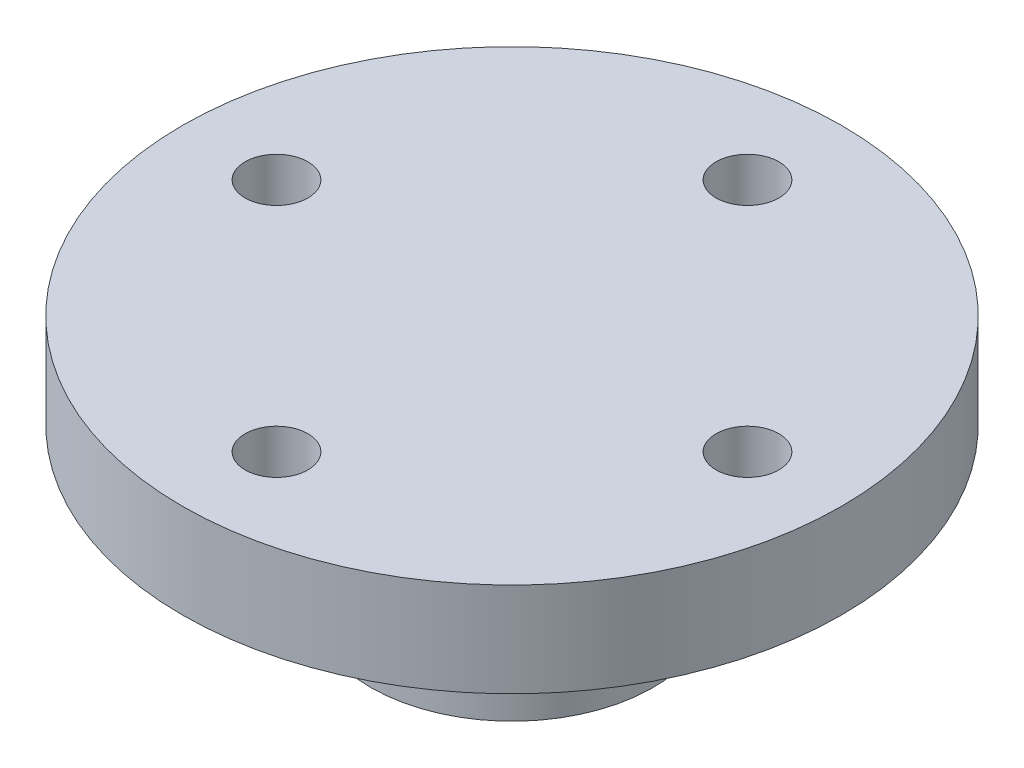
SolidWorks part; units mm, degrees
material "CA"
ref_plane "前视基准面" through (0, 0, 0) normal (0, 0, 1) x (1, 0, 0)
ref_plane "上视基准面" through (0, 0, 0) normal (0, 1, 0) x (1, 0, 0)
ref_plane "右视基准面" through (0, 0, 0) normal (1, 0, 0) x (0, 0, -1)
sketch "草图1" plane through (0, 0, 0) normal (0, 1, 0) x (1, 0, 0)
  circle A0 centre (0, 0) radius 4.5
  dimension "D1" = 9
extrude "凸台-拉伸1" add sketch "草图1" along normal blind 8
sketch "草图2" plane through (0, 8, 0) normal (0, 1, 0) x (1, 0, 0)
  circle A0 centre (0, 0) radius 10.5
  dimension "D1" = 21
extrude "凸台-拉伸2" add sketch "草图2" against normal blind 3
sketch "草图3" plane through (0, 0, 0) normal (0, -1, 0) x (1, 0, 0)
  circle A0 centre (0, 0) radius 2.8
  dimension "D1" = 5.6
extrude "切除-拉伸1" cut sketch "草图3" against normal blind 2.5
sketch "草图4" plane through (0, 0, 0) normal (0, -1, 0) x (1, 0, 0)
  line L0 (0.1306, 2.8722) -> (0.2304, 2.866)
  line L1 (-0.05, 2.8748) -> (0.05, 2.8748)
  line L2 (-0.05, 2.8748) -> (-0.05, 2.7252)
  line L3 (-0.05, 2.7252) -> (0.05, 2.7252)
  line L4 (0.05, 2.8748) -> (0.05, 2.7252)
  line L5 (-0.05, 2.8748) -> (0.05, 2.7252) construction
  line L6 (-0.05, 2.7252) -> (0.05, 2.8748) construction
  line L7 (0.1306, 2.8722) -> (0.1212, 2.723)
  line L8 (0.2304, 2.866) -> (0.221, 2.7167)
  line L9 (0.1212, 2.723) -> (0.221, 2.7167)
  line L10 (0.3107, 2.8584) -> (0.4099, 2.8458)
  line L11 (0.3107, 2.8584) -> (0.292, 2.71)
  line L12 (0.4099, 2.8458) -> (0.3912, 2.6975)
  line L13 (0.292, 2.71) -> (0.3912, 2.6975)
  line L14 (0.4896, 2.8332) -> (0.5878, 2.8145)
  line L15 (0.4896, 2.8332) -> (0.4615, 2.6863)
  line L16 (0.5878, 2.8145) -> (0.5598, 2.6676)
  line L17 (0.4615, 2.6863) -> (0.5598, 2.6676)
  line L18 (0.6665, 2.7969) -> (0.7634, 2.772)
  line L19 (0.6665, 2.7969) -> (0.6293, 2.6521)
  line L20 (0.7634, 2.772) -> (0.7262, 2.6272)
  line L21 (0.6293, 2.6521) -> (0.7262, 2.6272)
  line L22 (0.8408, 2.7495) -> (0.9359, 2.7186)
  line L23 (0.8408, 2.7495) -> (0.7946, 2.6073)
  line L24 (0.9359, 2.7186) -> (0.8897, 2.5764)
  line L25 (0.7946, 2.6073) -> (0.8897, 2.5764)
  line L26 (1.0118, 2.6913) -> (1.1048, 2.6545)
  line L27 (1.0118, 2.6913) -> (0.9567, 2.5523)
  line L28 (1.1048, 2.6545) -> (1.0497, 2.5155)
  line L29 (0.9567, 2.5523) -> (1.0497, 2.5155)
  line L30 (1.1788, 2.6225) -> (1.2693, 2.5799)
  line L31 (1.1788, 2.6225) -> (1.1151, 2.4872)
  line L32 (1.2693, 2.5799) -> (1.2056, 2.4446)
  line L33 (1.1151, 2.4872) -> (1.2056, 2.4446)
  line L34 (1.3411, 2.5433) -> (1.4287, 2.4951)
  line L35 (1.3411, 2.5433) -> (1.2691, 2.4122)
  line L36 (1.4287, 2.4951) -> (1.3567, 2.3641)
  line L37 (1.2691, 2.4122) -> (1.3567, 2.3641)
  line L38 (1.4982, 2.454) -> (1.5826, 2.4005)
  line L39 (1.4982, 2.454) -> (1.418, 2.3278)
  line L40 (1.5826, 2.4005) -> (1.5025, 2.2742)
  line L41 (1.418, 2.3278) -> (1.5025, 2.2742)
  line L42 (1.6493, 2.3551) -> (1.7302, 2.2963)
  line L43 (1.6493, 2.3551) -> (1.5614, 2.2342)
  line L44 (1.7302, 2.2963) -> (1.6423, 2.1754)
  line L45 (1.5614, 2.2342) -> (1.6423, 2.1754)
  line L46 (1.7939, 2.2469) -> (1.871, 2.1832)
  line L47 (1.7939, 2.2469) -> (1.6986, 2.1317)
  line L48 (1.871, 2.1832) -> (1.7757, 2.068)
  line L49 (1.6986, 2.1317) -> (1.7757, 2.068)
  line L50 (1.9315, 2.1298) -> (2.0044, 2.0614)
  line L51 (1.9315, 2.1298) -> (1.8291, 2.0208)
  line L52 (2.0044, 2.0614) -> (1.902, 1.9524)
  line L53 (1.8291, 2.0208) -> (1.902, 1.9524)
  line L54 (2.0614, 2.0044) -> (2.1298, 1.9315)
  line L55 (2.0614, 2.0044) -> (1.9524, 1.902)
  line L56 (2.1298, 1.9315) -> (2.0208, 1.8291)
  line L57 (1.9524, 1.902) -> (2.0208, 1.8291)
  line L58 (2.1832, 1.871) -> (2.2469, 1.7939)
  line L59 (2.1832, 1.871) -> (2.068, 1.7757)
  line L60 (2.2469, 1.7939) -> (2.1317, 1.6986)
  line L61 (2.068, 1.7757) -> (2.1317, 1.6986)
  line L62 (2.2963, 1.7302) -> (2.3551, 1.6493)
  line L63 (2.2963, 1.7302) -> (2.1754, 1.6423)
  line L64 (2.3551, 1.6493) -> (2.2342, 1.5614)
  line L65 (2.1754, 1.6423) -> (2.2342, 1.5614)
  line L66 (2.4005, 1.5826) -> (2.454, 1.4982)
  line L67 (2.4005, 1.5826) -> (2.2742, 1.5025)
  line L68 (2.454, 1.4982) -> (2.3278, 1.418)
  line L69 (2.2742, 1.5025) -> (2.3278, 1.418)
  line L70 (2.4951, 1.4287) -> (2.5433, 1.3411)
  line L71 (2.4951, 1.4287) -> (2.3641, 1.3567)
  line L72 (2.5433, 1.3411) -> (2.4122, 1.2691)
  line L73 (2.3641, 1.3567) -> (2.4122, 1.2691)
  line L74 (2.5799, 1.2693) -> (2.6225, 1.1788)
  line L75 (2.5799, 1.2693) -> (2.4446, 1.2056)
  line L76 (2.6225, 1.1788) -> (2.4872, 1.1151)
  line L77 (2.4446, 1.2056) -> (2.4872, 1.1151)
  line L78 (2.6545, 1.1048) -> (2.6913, 1.0118)
  line L79 (2.6545, 1.1048) -> (2.5155, 1.0497)
  line L80 (2.6913, 1.0118) -> (2.5523, 0.9567)
  line L81 (2.5155, 1.0497) -> (2.5523, 0.9567)
  line L82 (2.7186, 0.9359) -> (2.7495, 0.8408)
  line L83 (2.7186, 0.9359) -> (2.5764, 0.8897)
  line L84 (2.7495, 0.8408) -> (2.6073, 0.7946)
  line L85 (2.5764, 0.8897) -> (2.6073, 0.7946)
  line L86 (2.772, 0.7634) -> (2.7969, 0.6665)
  line L87 (2.772, 0.7634) -> (2.6272, 0.7262)
  line L88 (2.7969, 0.6665) -> (2.6521, 0.6293)
  line L89 (2.6272, 0.7262) -> (2.6521, 0.6293)
  line L90 (2.8145, 0.5878) -> (2.8332, 0.4896)
  line L91 (2.8145, 0.5878) -> (2.6676, 0.5598)
  line L92 (2.8332, 0.4896) -> (2.6863, 0.4615)
  line L93 (2.6676, 0.5598) -> (2.6863, 0.4615)
  line L94 (2.8458, 0.4099) -> (2.8584, 0.3107)
  line L95 (2.8458, 0.4099) -> (2.6975, 0.3912)
  line L96 (2.8584, 0.3107) -> (2.71, 0.292)
  line L97 (2.6975, 0.3912) -> (2.71, 0.292)
  line L98 (2.866, 0.2304) -> (2.8722, 0.1306)
  line L99 (2.866, 0.2304) -> (2.7167, 0.221)
  line L100 (2.8722, 0.1306) -> (2.723, 0.1212)
  line L101 (2.7167, 0.221) -> (2.723, 0.1212)
  line L102 (2.8748, 0.05) -> (2.8748, -0.05)
  line L103 (2.8748, 0.05) -> (2.7252, 0.05)
  line L104 (2.8748, -0.05) -> (2.7252, -0.05)
  line L105 (2.7252, 0.05) -> (2.7252, -0.05)
  line L106 (2.8722, -0.1306) -> (2.866, -0.2304)
  line L107 (2.8722, -0.1306) -> (2.723, -0.1212)
  line L108 (2.866, -0.2304) -> (2.7167, -0.221)
  line L109 (2.723, -0.1212) -> (2.7167, -0.221)
  line L110 (2.8584, -0.3107) -> (2.8458, -0.4099)
  line L111 (2.8584, -0.3107) -> (2.71, -0.292)
  line L112 (2.8458, -0.4099) -> (2.6975, -0.3912)
  line L113 (2.71, -0.292) -> (2.6975, -0.3912)
  line L114 (2.8332, -0.4896) -> (2.8145, -0.5878)
  line L115 (2.8332, -0.4896) -> (2.6863, -0.4615)
  line L116 (2.8145, -0.5878) -> (2.6676, -0.5598)
  line L117 (2.6863, -0.4615) -> (2.6676, -0.5598)
  line L118 (2.7969, -0.6665) -> (2.772, -0.7634)
  line L119 (2.7969, -0.6665) -> (2.6521, -0.6293)
  line L120 (2.772, -0.7634) -> (2.6272, -0.7262)
  line L121 (2.6521, -0.6293) -> (2.6272, -0.7262)
  line L122 (2.7495, -0.8408) -> (2.7186, -0.9359)
  line L123 (2.7495, -0.8408) -> (2.6073, -0.7946)
  line L124 (2.7186, -0.9359) -> (2.5764, -0.8897)
  line L125 (2.6073, -0.7946) -> (2.5764, -0.8897)
  line L126 (2.6913, -1.0118) -> (2.6545, -1.1048)
  line L127 (2.6913, -1.0118) -> (2.5523, -0.9567)
  line L128 (2.6545, -1.1048) -> (2.5155, -1.0497)
  line L129 (2.5523, -0.9567) -> (2.5155, -1.0497)
  line L130 (2.6225, -1.1788) -> (2.5799, -1.2693)
  line L131 (2.6225, -1.1788) -> (2.4872, -1.1151)
  line L132 (2.5799, -1.2693) -> (2.4446, -1.2056)
  line L133 (2.4872, -1.1151) -> (2.4446, -1.2056)
  line L134 (2.5433, -1.3411) -> (2.4951, -1.4287)
  line L135 (2.5433, -1.3411) -> (2.4122, -1.2691)
  line L136 (2.4951, -1.4287) -> (2.3641, -1.3567)
  line L137 (2.4122, -1.2691) -> (2.3641, -1.3567)
  line L138 (2.454, -1.4982) -> (2.4005, -1.5826)
  line L139 (2.454, -1.4982) -> (2.3278, -1.418)
  line L140 (2.4005, -1.5826) -> (2.2742, -1.5025)
  line L141 (2.3278, -1.418) -> (2.2742, -1.5025)
  line L142 (2.3551, -1.6493) -> (2.2963, -1.7302)
  line L143 (2.3551, -1.6493) -> (2.2342, -1.5614)
  line L144 (2.2963, -1.7302) -> (2.1754, -1.6423)
  line L145 (2.2342, -1.5614) -> (2.1754, -1.6423)
  line L146 (2.2469, -1.7939) -> (2.1832, -1.871)
  line L147 (2.2469, -1.7939) -> (2.1317, -1.6986)
  line L148 (2.1832, -1.871) -> (2.068, -1.7757)
  line L149 (2.1317, -1.6986) -> (2.068, -1.7757)
  line L150 (2.1298, -1.9315) -> (2.0614, -2.0044)
  line L151 (2.1298, -1.9315) -> (2.0208, -1.8291)
  line L152 (2.0614, -2.0044) -> (1.9524, -1.902)
  line L153 (2.0208, -1.8291) -> (1.9524, -1.902)
  line L154 (2.0044, -2.0614) -> (1.9315, -2.1298)
  line L155 (2.0044, -2.0614) -> (1.902, -1.9524)
  line L156 (1.9315, -2.1298) -> (1.8291, -2.0208)
  line L157 (1.902, -1.9524) -> (1.8291, -2.0208)
  line L158 (1.871, -2.1832) -> (1.7939, -2.2469)
  line L159 (1.871, -2.1832) -> (1.7757, -2.068)
  line L160 (1.7939, -2.2469) -> (1.6986, -2.1317)
  line L161 (1.7757, -2.068) -> (1.6986, -2.1317)
  line L162 (1.7302, -2.2963) -> (1.6493, -2.3551)
  line L163 (1.7302, -2.2963) -> (1.6423, -2.1754)
  line L164 (1.6493, -2.3551) -> (1.5614, -2.2342)
  line L165 (1.6423, -2.1754) -> (1.5614, -2.2342)
  line L166 (1.5826, -2.4005) -> (1.4982, -2.454)
  line L167 (1.5826, -2.4005) -> (1.5025, -2.2742)
  line L168 (1.4982, -2.454) -> (1.418, -2.3278)
  line L169 (1.5025, -2.2742) -> (1.418, -2.3278)
  line L170 (1.4287, -2.4951) -> (1.3411, -2.5433)
  line L171 (1.4287, -2.4951) -> (1.3567, -2.3641)
  line L172 (1.3411, -2.5433) -> (1.2691, -2.4122)
  line L173 (1.3567, -2.3641) -> (1.2691, -2.4122)
  line L174 (1.2693, -2.5799) -> (1.1788, -2.6225)
  line L175 (1.2693, -2.5799) -> (1.2056, -2.4446)
  line L176 (1.1788, -2.6225) -> (1.1151, -2.4872)
  line L177 (1.2056, -2.4446) -> (1.1151, -2.4872)
  line L178 (1.1048, -2.6545) -> (1.0118, -2.6913)
  line L179 (1.1048, -2.6545) -> (1.0497, -2.5155)
  line L180 (1.0118, -2.6913) -> (0.9567, -2.5523)
  line L181 (1.0497, -2.5155) -> (0.9567, -2.5523)
  line L182 (0.9359, -2.7186) -> (0.8408, -2.7495)
  line L183 (0.9359, -2.7186) -> (0.8897, -2.5764)
  line L184 (0.8408, -2.7495) -> (0.7946, -2.6073)
  line L185 (0.8897, -2.5764) -> (0.7946, -2.6073)
  line L186 (0.7634, -2.772) -> (0.6665, -2.7969)
  line L187 (0.7634, -2.772) -> (0.7262, -2.6272)
  line L188 (0.6665, -2.7969) -> (0.6293, -2.6521)
  line L189 (0.7262, -2.6272) -> (0.6293, -2.6521)
  line L190 (0.5878, -2.8145) -> (0.4896, -2.8332)
  line L191 (0.5878, -2.8145) -> (0.5598, -2.6676)
  line L192 (0.4896, -2.8332) -> (0.4615, -2.6863)
  line L193 (0.5598, -2.6676) -> (0.4615, -2.6863)
  line L194 (0.4099, -2.8458) -> (0.3107, -2.8584)
  line L195 (0.4099, -2.8458) -> (0.3912, -2.6975)
  line L196 (0.3107, -2.8584) -> (0.292, -2.71)
  line L197 (0.3912, -2.6975) -> (0.292, -2.71)
  line L198 (0.2304, -2.866) -> (0.1306, -2.8722)
  line L199 (0.2304, -2.866) -> (0.221, -2.7167)
  line L200 (0.1306, -2.8722) -> (0.1212, -2.723)
  line L201 (0.221, -2.7167) -> (0.1212, -2.723)
  line L202 (0.05, -2.8748) -> (-0.05, -2.8748)
  line L203 (0.05, -2.8748) -> (0.05, -2.7252)
  line L204 (-0.05, -2.8748) -> (-0.05, -2.7252)
  line L205 (0.05, -2.7252) -> (-0.05, -2.7252)
  line L206 (-0.1306, -2.8722) -> (-0.2304, -2.866)
  line L207 (-0.1306, -2.8722) -> (-0.1212, -2.723)
  line L208 (-0.2304, -2.866) -> (-0.221, -2.7167)
  line L209 (-0.1212, -2.723) -> (-0.221, -2.7167)
  line L210 (-0.3107, -2.8584) -> (-0.4099, -2.8458)
  line L211 (-0.3107, -2.8584) -> (-0.292, -2.71)
  line L212 (-0.4099, -2.8458) -> (-0.3912, -2.6975)
  line L213 (-0.292, -2.71) -> (-0.3912, -2.6975)
  line L214 (-0.4896, -2.8332) -> (-0.5878, -2.8145)
  line L215 (-0.4896, -2.8332) -> (-0.4615, -2.6863)
  line L216 (-0.5878, -2.8145) -> (-0.5598, -2.6676)
  line L217 (-0.4615, -2.6863) -> (-0.5598, -2.6676)
  line L218 (-0.6665, -2.7969) -> (-0.7634, -2.772)
  line L219 (-0.6665, -2.7969) -> (-0.6293, -2.6521)
  line L220 (-0.7634, -2.772) -> (-0.7262, -2.6272)
  line L221 (-0.6293, -2.6521) -> (-0.7262, -2.6272)
  line L222 (-0.8408, -2.7495) -> (-0.9359, -2.7186)
  line L223 (-0.8408, -2.7495) -> (-0.7946, -2.6073)
  line L224 (-0.9359, -2.7186) -> (-0.8897, -2.5764)
  line L225 (-0.7946, -2.6073) -> (-0.8897, -2.5764)
  line L226 (-1.0118, -2.6913) -> (-1.1048, -2.6545)
  line L227 (-1.0118, -2.6913) -> (-0.9567, -2.5523)
  line L228 (-1.1048, -2.6545) -> (-1.0497, -2.5155)
  line L229 (-0.9567, -2.5523) -> (-1.0497, -2.5155)
  line L230 (-1.1788, -2.6225) -> (-1.2693, -2.5799)
  line L231 (-1.1788, -2.6225) -> (-1.1151, -2.4872)
  line L232 (-1.2693, -2.5799) -> (-1.2056, -2.4446)
  line L233 (-1.1151, -2.4872) -> (-1.2056, -2.4446)
  line L234 (-1.3411, -2.5433) -> (-1.4287, -2.4951)
  line L235 (-1.3411, -2.5433) -> (-1.2691, -2.4122)
  line L236 (-1.4287, -2.4951) -> (-1.3567, -2.3641)
  line L237 (-1.2691, -2.4122) -> (-1.3567, -2.3641)
  line L238 (-1.4982, -2.454) -> (-1.5826, -2.4005)
  line L239 (-1.4982, -2.454) -> (-1.418, -2.3278)
  line L240 (-1.5826, -2.4005) -> (-1.5025, -2.2742)
  line L241 (-1.418, -2.3278) -> (-1.5025, -2.2742)
  line L242 (-1.6493, -2.3551) -> (-1.7302, -2.2963)
  line L243 (-1.6493, -2.3551) -> (-1.5614, -2.2342)
  line L244 (-1.7302, -2.2963) -> (-1.6423, -2.1754)
  line L245 (-1.5614, -2.2342) -> (-1.6423, -2.1754)
  line L246 (-1.7939, -2.2469) -> (-1.871, -2.1832)
  line L247 (-1.7939, -2.2469) -> (-1.6986, -2.1317)
  line L248 (-1.871, -2.1832) -> (-1.7757, -2.068)
  line L249 (-1.6986, -2.1317) -> (-1.7757, -2.068)
  line L250 (-1.9315, -2.1298) -> (-2.0044, -2.0614)
  line L251 (-1.9315, -2.1298) -> (-1.8291, -2.0208)
  line L252 (-2.0044, -2.0614) -> (-1.902, -1.9524)
  line L253 (-1.8291, -2.0208) -> (-1.902, -1.9524)
  line L254 (-2.0614, -2.0044) -> (-2.1298, -1.9315)
  line L255 (-2.0614, -2.0044) -> (-1.9524, -1.902)
  line L256 (-2.1298, -1.9315) -> (-2.0208, -1.8291)
  line L257 (-1.9524, -1.902) -> (-2.0208, -1.8291)
  line L258 (-2.1832, -1.871) -> (-2.2469, -1.7939)
  line L259 (-2.1832, -1.871) -> (-2.068, -1.7757)
  line L260 (-2.2469, -1.7939) -> (-2.1317, -1.6986)
  line L261 (-2.068, -1.7757) -> (-2.1317, -1.6986)
  line L262 (-2.2963, -1.7302) -> (-2.3551, -1.6493)
  line L263 (-2.2963, -1.7302) -> (-2.1754, -1.6423)
  line L264 (-2.3551, -1.6493) -> (-2.2342, -1.5614)
  line L265 (-2.1754, -1.6423) -> (-2.2342, -1.5614)
  line L266 (-2.4005, -1.5826) -> (-2.454, -1.4982)
  line L267 (-2.4005, -1.5826) -> (-2.2742, -1.5025)
  line L268 (-2.454, -1.4982) -> (-2.3278, -1.418)
  line L269 (-2.2742, -1.5025) -> (-2.3278, -1.418)
  line L270 (-2.4951, -1.4287) -> (-2.5433, -1.3411)
  line L271 (-2.4951, -1.4287) -> (-2.3641, -1.3567)
  line L272 (-2.5433, -1.3411) -> (-2.4122, -1.2691)
  line L273 (-2.3641, -1.3567) -> (-2.4122, -1.2691)
  line L274 (-2.5799, -1.2693) -> (-2.6225, -1.1788)
  line L275 (-2.5799, -1.2693) -> (-2.4446, -1.2056)
  line L276 (-2.6225, -1.1788) -> (-2.4872, -1.1151)
  line L277 (-2.4446, -1.2056) -> (-2.4872, -1.1151)
  line L278 (-2.6545, -1.1048) -> (-2.6913, -1.0118)
  line L279 (-2.6545, -1.1048) -> (-2.5155, -1.0497)
  line L280 (-2.6913, -1.0118) -> (-2.5523, -0.9567)
  line L281 (-2.5155, -1.0497) -> (-2.5523, -0.9567)
  line L282 (-2.7186, -0.9359) -> (-2.7495, -0.8408)
  line L283 (-2.7186, -0.9359) -> (-2.5764, -0.8897)
  line L284 (-2.7495, -0.8408) -> (-2.6073, -0.7946)
  line L285 (-2.5764, -0.8897) -> (-2.6073, -0.7946)
  line L286 (-2.772, -0.7634) -> (-2.7969, -0.6665)
  line L287 (-2.772, -0.7634) -> (-2.6272, -0.7262)
  line L288 (-2.7969, -0.6665) -> (-2.6521, -0.6293)
  line L289 (-2.6272, -0.7262) -> (-2.6521, -0.6293)
  line L290 (-2.8145, -0.5878) -> (-2.8332, -0.4896)
  line L291 (-2.8145, -0.5878) -> (-2.6676, -0.5598)
  line L292 (-2.8332, -0.4896) -> (-2.6863, -0.4615)
  line L293 (-2.6676, -0.5598) -> (-2.6863, -0.4615)
  line L294 (-2.8458, -0.4099) -> (-2.8584, -0.3107)
  line L295 (-2.8458, -0.4099) -> (-2.6975, -0.3912)
  line L296 (-2.8584, -0.3107) -> (-2.71, -0.292)
  line L297 (-2.6975, -0.3912) -> (-2.71, -0.292)
  line L298 (-2.866, -0.2304) -> (-2.8722, -0.1306)
  line L299 (-2.866, -0.2304) -> (-2.7167, -0.221)
  line L300 (-2.8722, -0.1306) -> (-2.723, -0.1212)
  line L301 (-2.7167, -0.221) -> (-2.723, -0.1212)
  line L302 (-2.8748, -0.05) -> (-2.8748, 0.05)
  line L303 (-2.8748, -0.05) -> (-2.7252, -0.05)
  line L304 (-2.8748, 0.05) -> (-2.7252, 0.05)
  line L305 (-2.7252, -0.05) -> (-2.7252, 0.05)
  line L306 (-2.8722, 0.1306) -> (-2.866, 0.2304)
  line L307 (-2.8722, 0.1306) -> (-2.723, 0.1212)
  line L308 (-2.866, 0.2304) -> (-2.7167, 0.221)
  line L309 (-2.723, 0.1212) -> (-2.7167, 0.221)
  line L310 (-2.8584, 0.3107) -> (-2.8458, 0.4099)
  line L311 (-2.8584, 0.3107) -> (-2.71, 0.292)
  line L312 (-2.8458, 0.4099) -> (-2.6975, 0.3912)
  line L313 (-2.71, 0.292) -> (-2.6975, 0.3912)
  line L314 (-2.8332, 0.4896) -> (-2.8145, 0.5878)
  line L315 (-2.8332, 0.4896) -> (-2.6863, 0.4615)
  line L316 (-2.8145, 0.5878) -> (-2.6676, 0.5598)
  line L317 (-2.6863, 0.4615) -> (-2.6676, 0.5598)
  line L318 (-2.7969, 0.6665) -> (-2.772, 0.7634)
  line L319 (-2.7969, 0.6665) -> (-2.6521, 0.6293)
  line L320 (-2.772, 0.7634) -> (-2.6272, 0.7262)
  line L321 (-2.6521, 0.6293) -> (-2.6272, 0.7262)
  line L322 (-2.7495, 0.8408) -> (-2.7186, 0.9359)
  line L323 (-2.7495, 0.8408) -> (-2.6073, 0.7946)
  line L324 (-2.7186, 0.9359) -> (-2.5764, 0.8897)
  line L325 (-2.6073, 0.7946) -> (-2.5764, 0.8897)
  line L326 (-2.6913, 1.0118) -> (-2.6545, 1.1048)
  line L327 (-2.6913, 1.0118) -> (-2.5523, 0.9567)
  line L328 (-2.6545, 1.1048) -> (-2.5155, 1.0497)
  line L329 (-2.5523, 0.9567) -> (-2.5155, 1.0497)
  line L330 (-2.6225, 1.1788) -> (-2.5799, 1.2693)
  line L331 (-2.6225, 1.1788) -> (-2.4872, 1.1151)
  line L332 (-2.5799, 1.2693) -> (-2.4446, 1.2056)
  line L333 (-2.4872, 1.1151) -> (-2.4446, 1.2056)
  line L334 (-2.5433, 1.3411) -> (-2.4951, 1.4287)
  line L335 (-2.5433, 1.3411) -> (-2.4122, 1.2691)
  line L336 (-2.4951, 1.4287) -> (-2.3641, 1.3567)
  line L337 (-2.4122, 1.2691) -> (-2.3641, 1.3567)
  line L338 (-2.454, 1.4982) -> (-2.4005, 1.5826)
  line L339 (-2.454, 1.4982) -> (-2.3278, 1.418)
  line L340 (-2.4005, 1.5826) -> (-2.2742, 1.5025)
  line L341 (-2.3278, 1.418) -> (-2.2742, 1.5025)
  line L342 (-2.3551, 1.6493) -> (-2.2963, 1.7302)
  line L343 (-2.3551, 1.6493) -> (-2.2342, 1.5614)
  line L344 (-2.2963, 1.7302) -> (-2.1754, 1.6423)
  line L345 (-2.2342, 1.5614) -> (-2.1754, 1.6423)
  line L346 (-2.2469, 1.7939) -> (-2.1832, 1.871)
  line L347 (-2.2469, 1.7939) -> (-2.1317, 1.6986)
  line L348 (-2.1832, 1.871) -> (-2.068, 1.7757)
  line L349 (-2.1317, 1.6986) -> (-2.068, 1.7757)
  line L350 (-2.1298, 1.9315) -> (-2.0614, 2.0044)
  line L351 (-2.1298, 1.9315) -> (-2.0208, 1.8291)
  line L352 (-2.0614, 2.0044) -> (-1.9524, 1.902)
  line L353 (-2.0208, 1.8291) -> (-1.9524, 1.902)
  line L354 (-2.0044, 2.0614) -> (-1.9315, 2.1298)
  line L355 (-2.0044, 2.0614) -> (-1.902, 1.9524)
  line L356 (-1.9315, 2.1298) -> (-1.8291, 2.0208)
  line L357 (-1.902, 1.9524) -> (-1.8291, 2.0208)
  line L358 (-1.871, 2.1832) -> (-1.7939, 2.2469)
  line L359 (-1.871, 2.1832) -> (-1.7757, 2.068)
  line L360 (-1.7939, 2.2469) -> (-1.6986, 2.1317)
  line L361 (-1.7757, 2.068) -> (-1.6986, 2.1317)
  line L362 (-1.7302, 2.2963) -> (-1.6493, 2.3551)
  line L363 (-1.7302, 2.2963) -> (-1.6423, 2.1754)
  line L364 (-1.6493, 2.3551) -> (-1.5614, 2.2342)
  line L365 (-1.6423, 2.1754) -> (-1.5614, 2.2342)
  line L366 (-1.5826, 2.4005) -> (-1.4982, 2.454)
  line L367 (-1.5826, 2.4005) -> (-1.5025, 2.2742)
  line L368 (-1.4982, 2.454) -> (-1.418, 2.3278)
  line L369 (-1.5025, 2.2742) -> (-1.418, 2.3278)
  line L370 (-1.4287, 2.4951) -> (-1.3411, 2.5433)
  line L371 (-1.4287, 2.4951) -> (-1.3567, 2.3641)
  line L372 (-1.3411, 2.5433) -> (-1.2691, 2.4122)
  line L373 (-1.3567, 2.3641) -> (-1.2691, 2.4122)
  line L374 (-1.2693, 2.5799) -> (-1.1788, 2.6225)
  line L375 (-1.2693, 2.5799) -> (-1.2056, 2.4446)
  line L376 (-1.1788, 2.6225) -> (-1.1151, 2.4872)
  line L377 (-1.2056, 2.4446) -> (-1.1151, 2.4872)
  line L378 (-1.1048, 2.6545) -> (-1.0118, 2.6913)
  line L379 (-1.1048, 2.6545) -> (-1.0497, 2.5155)
  line L380 (-1.0118, 2.6913) -> (-0.9567, 2.5523)
  line L381 (-1.0497, 2.5155) -> (-0.9567, 2.5523)
  line L382 (-0.9359, 2.7186) -> (-0.8408, 2.7495)
  line L383 (-0.9359, 2.7186) -> (-0.8897, 2.5764)
  line L384 (-0.8408, 2.7495) -> (-0.7946, 2.6073)
  line L385 (-0.8897, 2.5764) -> (-0.7946, 2.6073)
  line L386 (-0.7634, 2.772) -> (-0.6665, 2.7969)
  line L387 (-0.7634, 2.772) -> (-0.7262, 2.6272)
  line L388 (-0.6665, 2.7969) -> (-0.6293, 2.6521)
  line L389 (-0.7262, 2.6272) -> (-0.6293, 2.6521)
  line L390 (-0.5878, 2.8145) -> (-0.4896, 2.8332)
  line L391 (-0.5878, 2.8145) -> (-0.5598, 2.6676)
  line L392 (-0.4896, 2.8332) -> (-0.4615, 2.6863)
  line L393 (-0.5598, 2.6676) -> (-0.4615, 2.6863)
  line L394 (-0.4099, 2.8458) -> (-0.3107, 2.8584)
  line L395 (-0.4099, 2.8458) -> (-0.3912, 2.6975)
  line L396 (-0.3107, 2.8584) -> (-0.292, 2.71)
  line L397 (-0.3912, 2.6975) -> (-0.292, 2.71)
  line L398 (-0.2304, 2.866) -> (-0.1306, 2.8722)
  line L399 (-0.2304, 2.866) -> (-0.221, 2.7167)
  line L400 (-0.1306, 2.8722) -> (-0.1212, 2.723)
  line L401 (-0.221, 2.7167) -> (-0.1212, 2.723)
  circle A0 centre (0, 0) radius 2.8 construction
  circle A1 centre (0, 0) radius 2.8 construction
  point P0 (0, 2.8)
  point P409 (0, 0)
  dimension "D1" = 0.1
  dimension "D2" = 100
extrude "切除-拉伸2" cut sketch "草图4" against normal blind 2.5
sketch "草图5" plane through (0, 8, 0) normal (0, 1, 0) x (1, 0, 0)
  circle A0 centre (0, 7.5) radius 1
  circle A1 centre (0, 0) radius 10.5 construction
  circle A2 centre (7.5, 0) radius 1
  circle A3 centre (0, -7.5) radius 1
  circle A4 centre (-7.5, 0) radius 1
  point P14 (0, 0)
  dimension "D1" = 2
  dimension "D2" = 7.5
  dimension "D3" = 4
extrude "切除-拉伸3" cut sketch "草图5" against normal up to next
